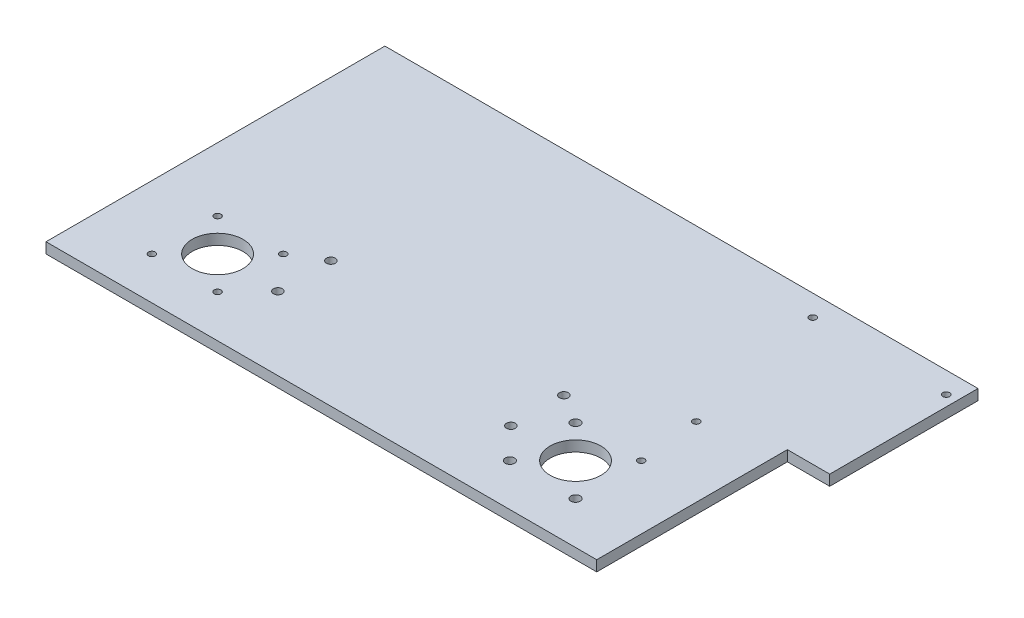
SolidWorks part; units mm, degrees
ref_plane "前视基准面" through (0, 0, 0) normal (0, 0, 1) x (1, 0, 0)
ref_plane "上视基准面" through (0, 0, 0) normal (0, 1, 0) x (1, 0, 0)
ref_plane "右视基准面" through (0, 0, 0) normal (1, 0, 0) x (0, 0, -1)
sketch "草图1" plane through (0, 0, 0) normal (0, 1, 0) x (1, 0, 0)
  line L0 (-79, -60) -> (-110, -60) construction
  line L1 (-140, -80) -> (140, -80)
  line L2 (-140, -80) -> (-140, 80)
  line L3 (-140, 80) -> (140, 80)
  line L4 (140, -80) -> (140, 80)
  line L5 (-140, -80) -> (140, 80) construction
  line L6 (-140, 80) -> (140, -80) construction
  line L7 (140, -80) -> (120, -80)
  line L8 (140, -80) -> (140, 10)
  line L9 (140, 10) -> (120, 10)
  line L10 (120, -80) -> (120, 10)
  line L11 (90, -60) -> (59, -60) construction
  line L12 (90, -60) -> (90, -29) construction
  line L13 (90, -29) -> (59, -29) construction
  line L14 (59, -60) -> (59, -29) construction
  line L15 (90, -60) -> (59, -29) construction
  line L16 (90, -29) -> (59, -60) construction
  line L17 (-79, -60) -> (-79, -29) construction
  line L18 (-79, -29) -> (-110, -29) construction
  line L19 (-110, -60) -> (-110, -29) construction
  line L20 (-79, -60) -> (-110, -29) construction
  line L21 (-79, -29) -> (-110, -60) construction
  line L23 (45, -20.5) -> (-65, -20.5) construction
  line L24 (45, -20.5) -> (45, -45.5) construction
  line L25 (45, -45.5) -> (-65, -45.5) construction
  line L26 (-65, -20.5) -> (-65, -45.5) construction
  circle A0 centre (90, -29) radius 1.6
  circle A1 centre (59, -29) radius 2.2
  circle A2 centre (90, -60) radius 2.2
  circle A3 centre (59, -60) radius 2.2
  circle A4 centre (-79, -29) radius 1.6
  circle A5 centre (-110, -29) radius 1.6
  circle A6 centre (-79, -60) radius 1.6
  circle A7 centre (-110, -60) radius 1.6
  circle A8 centre (45, -20.5) radius 2.1
  circle A9 centre (45, -45.5) radius 2.1
  circle A10 centre (-65, -45.5) radius 2.1
  circle A11 centre (-65, -20.5) radius 2.1
  circle A14 centre (74.5, -44.5) radius 12
  circle A15 centre (-94.5, -44.5) radius 12
  circle A19 centre (87, 0) radius 1.6
  circle A20 centre (72, 70) radius 1.6
  circle A21 centre (135, 70) radius 1.6
  point P0 (0, 0)
  point P9 (0, 0)
  point P30 (74.5, -44.5)
  point P31 (0, 0)
  point P39 (0, 0)
  point P42 (0, 0)
  point P44 (0, 0)
  point P46 (0, 0)
  point P50 (72, -44.5)
  point P51 (74.5, -44.5)
  dimension "D9" = 3.2
  dimension "D10" = 4.4
  dimension "D11" = 4.4
  dimension "D12" = 4.4
  dimension "D17" = 3.2
  dimension "D18" = 3.2
  dimension "D19" = 3.2
  dimension "D20" = 3.2
  dimension "D25" = 4.2
  dimension "D26" = 4.2
  dimension "D27" = 4.2
  dimension "D28" = 4.2
  dimension "D29" = 24
  dimension "D30" = 24
  dimension "D34" = 68
  dimension "D35" = 53
  dimension "D36" = 80
  dimension "D37" = 3.2
  dimension "D38" = 3.2
  dimension "D39" = 3.2
  dimension "D1" = 280
  dimension "D2" = 160
  dimension "D3" = 20
  dimension "D4" = 90
  dimension "D5" = 31
  dimension "D6" = 31
  dimension "D7" = 20
  dimension "D8" = 50
  dimension "D13" = 31
  dimension "D14" = 31
  dimension "D15" = 20
  dimension "D16" = 30
  dimension "D21" = 110
  dimension "D22" = 34.5
  dimension "D23" = 14
  dimension "D24" = 25
  dimension "D31" = 5
  dimension "D32" = 10
  dimension "D33" = 10
extrude "凸台-拉伸1" add sketch "草图1" along normal blind 5 contours L1 L10 L9 L4 L3 L2
